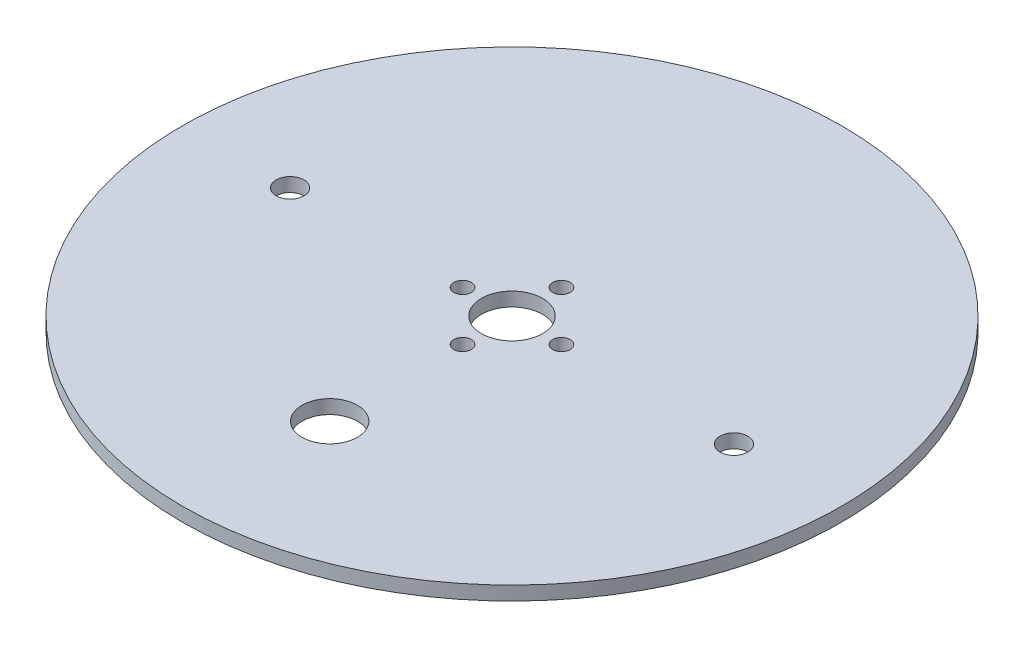
SolidWorks part; units mm, degrees
ref_plane "Front Plane" through (0, 0, 0) normal (0, 0, 1) x (1, 0, 0)
ref_plane "Top Plane" through (0, 0, 0) normal (0, 1, 0) x (1, 0, 0)
ref_plane "Right Plane" through (0, 0, 0) normal (1, 0, 0) x (0, 0, -1)
sketch "Sketch1" plane through (0, 0, 0) normal (0, 1, 0) x (1, 0, 0)
  circle A0 centre (0, 0) radius 75.438
extrude "Boss-Extrude1" add sketch "Sketch1" along normal blind 3.175
sketch "Sketch2" plane through (0, 3.175, 0) normal (0, 1, 0) x (1, 0, 0)
  line L0 (-50.8, 0) -> (50.8, 0) construction
  line L1 (0, -55) -> (0, 55) construction
  circle A0 centre (50.8, 0) radius 3.175
  circle A1 centre (-50.8, 0) radius 3.175
  point P7 (0, 0)
  dimension "D2" = 6.35
  dimension "D1" = 50.8
extrude "Cut-Extrude1" cut sketch "Sketch2" against normal through all
sketch "Sketch3" plane through (0, 3.175, 0) normal (0, 1, 0) x (1, 0, 0)
  circle A0 centre (0, 0) radius 7 construction
  circle A1 centre (0, -11.314) radius 2 construction
  circle A2 centre (-11.314, 0) radius 2 construction
  circle A3 centre (11.314, 0) radius 2 construction
  circle A4 centre (0, 11.314) radius 2 construction
  circle A5 centre (0, 0) radius 7
  circle A6 centre (0, -11.314) radius 2
  circle A7 centre (-11.314, 0) radius 2
  circle A8 centre (11.314, 0) radius 2
  circle A9 centre (0, 11.314) radius 2
extrude "Cut-Extrude2" cut sketch "Sketch3" against normal through all
hole_wizard "1/2 (0.5) Diameter Hole1" positions "Sketch4" profile "Sketch5" hole size "1/2" standard "ANSI Inch" end condition up to next
sketch "Sketch4" plane through (0, 3.175, 0) normal (0, 1, 0) x (1, 0, 0)
  point P0 (0, -41.7338)
sketch "Sketch5" plane through (0, 3.175, 41.7338) normal (1, 0, 0) x (0, 0, 1)
  line L0 (0, 0) -> (0, 3.175)
  line L1 (0, 3.175) -> (6.35, 3.175)
  line L2 (6.35, 3.175) -> (6.35, 0)
  line L5 (6.35, 0) -> (0, 0)
  line L11 (0, -6.35) -> (0, 107.95) construction
  dimension "Thru Hole Dia." = 12.7
  dimension "Thru Hole Depth" = 3.175
